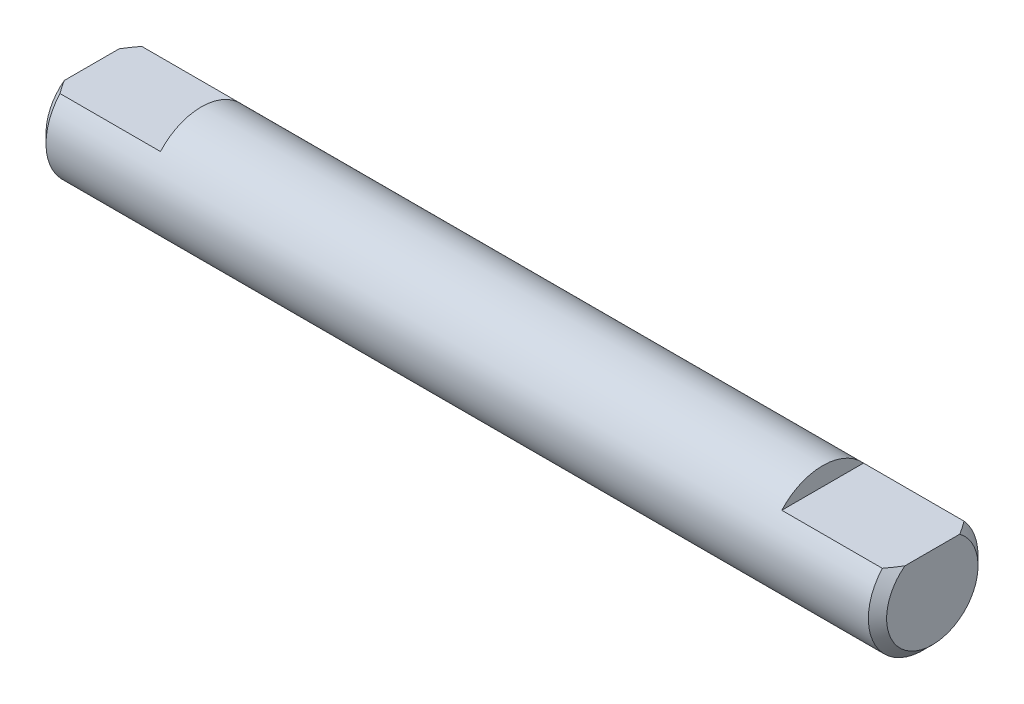
SolidWorks part; units mm, degrees
ref_plane "Front Plane" through (0, 0, 0) normal (0, 0, 1) x (1, 0, 0)
ref_plane "Top Plane" through (0, 0, 0) normal (0, 1, 0) x (1, 0, 0)
ref_plane "Right Plane" through (0, 0, 0) normal (1, 0, 0) x (0, 0, -1)
sketch "Sketch1" plane through (0, 0, 0) normal (1, 0, 0) x (0, 0, -1)
  circle A0 centre (0, 0) radius 3
  dimension "D1" = 6
extrude "Boss-Extrude1" add sketch "Sketch1" along normal mid plane 46
chamfer "Chamfer1" distance 0.5 angle 45 2 edges at (-23, 0, -3) (23, 0, -3)
sketch "Sketch2" plane through (23, 0, 0) normal (1, 0, 0) x (0, 0, -1)
  line L0 (-2.2361, 2) -> (2.2361, 2)
  circle A0 centre (0, 0) radius 3 construction
  arc A1 (2.2361, 2) -> (-2.2361, 2) centre (0, 0) ccw
  dimension "D1" = 2
extrude "Cut-Extrude1" cut sketch "Sketch2" against normal blind 6
mirror "Mirror1" about plane through (0, 0, 0) normal (1, 0, 0) of "Cut-Extrude1"
